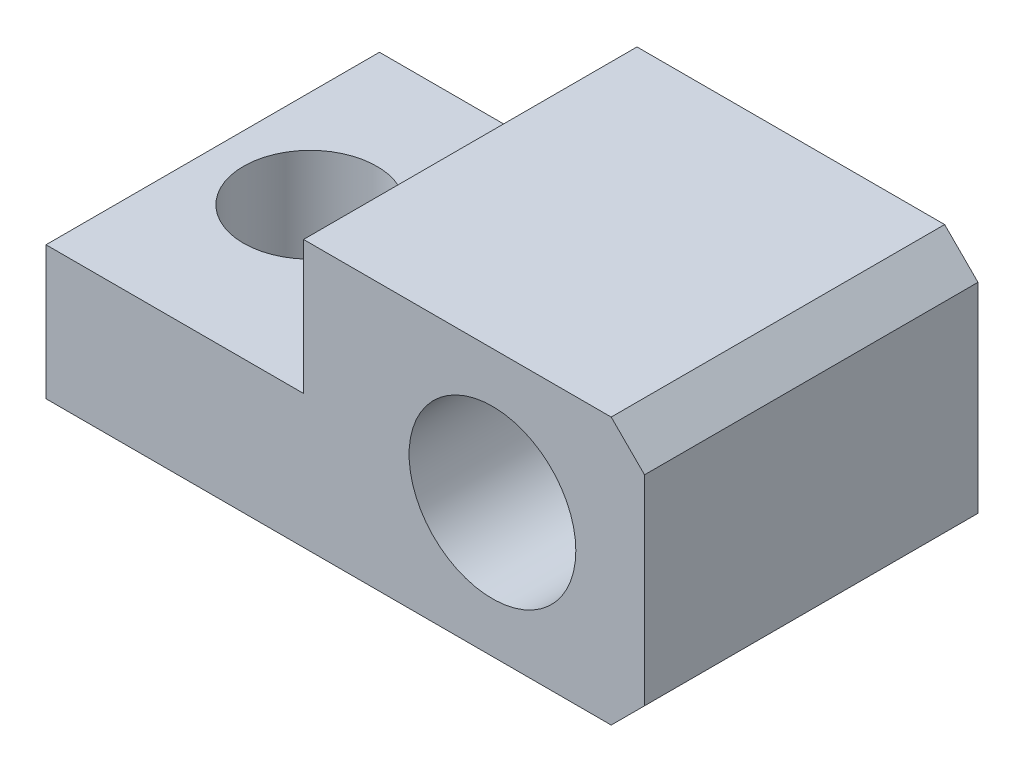
SolidWorks part; units mm, degrees
ref_plane "Спереди" through (0, 0, 0) normal (0, 0, 1) x (1, 0, 0)
ref_plane "Сверху" through (0, 0, 0) normal (0, 1, 0) x (1, 0, 0)
ref_plane "Справа" through (0, 0, 0) normal (1, 0, 0) x (0, 0, -1)
sketch "Эскиз1" plane through (0, 0, 0) normal (0, 0, 1) x (1, 0, 0)
  line L0 (3.5608, 4) -> (4.5608, 3)
  line L1 (-5.6654, 4) -> (3.5608, 4)
  line L2 (-13.389, 0) -> (-13.389, -4)
  line L3 (-13.389, -4) -> (3.5608, -4)
  line L4 (4.5608, 3) -> (4.5608, -3)
  line L5 (3.5608, -4) -> (4.5608, -3)
  line L8 (-5.6654, 0) -> (-13.389, 0)
  line L9 (-5.6654, 0) -> (-5.6654, 4)
  circle A0 centre (0, 0) radius 2.5
  point P3 (4.5608, -4)
  point P6 (4.5608, 4)
extrude "Вытянуть1" add sketch "Эскиз1" along normal blind 10
sketch "Эскиз2" plane through (0, 0, 0) normal (0, 1, 0) x (-1, 0, 0)
  circle A0 centre (10.4668, 5) radius 2
extrude "Вытянуть2" cut sketch "Эскиз2" against normal through all
